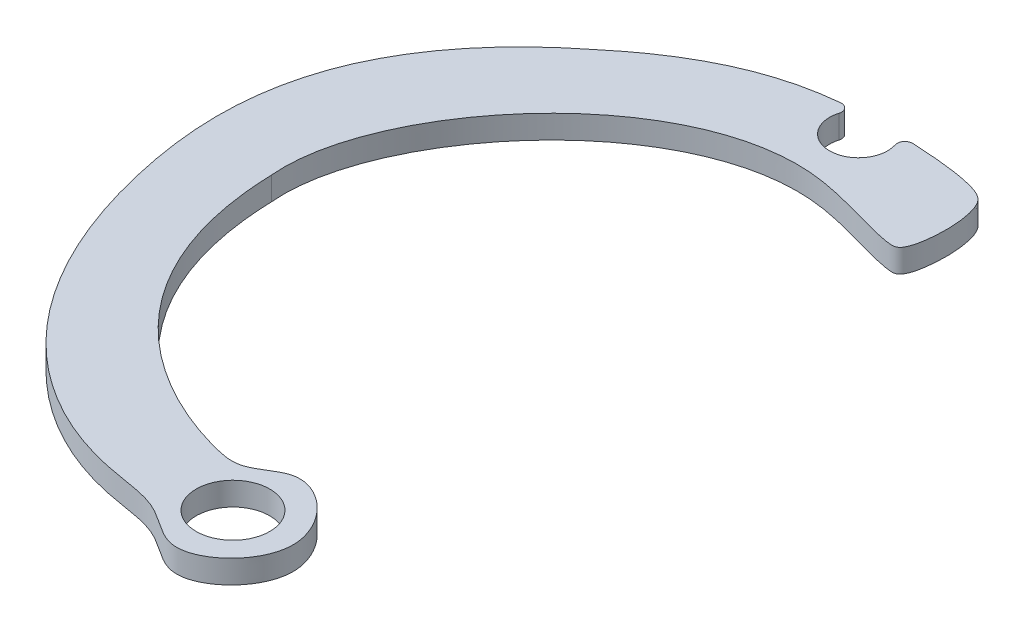
SolidWorks part; units mm, degrees
ref_plane "Front Plane" through (0, 0, 0) normal (0, 0, 1) x (1, 0, 0)
ref_plane "Top Plane" through (0, 0, 0) normal (0, 1, 0) x (1, 0, 0)
ref_plane "Right Plane" through (0, 0, 0) normal (1, 0, 0) x (0, 0, -1)
sketch "Sketch1" plane through (0, 0, 0) normal (0, 1, 0) x (1, 0, 0)
  line L1 (-28, 35) -> (28, 35) construction
  line L2 (-28, 35) -> (-28, 55) construction
  line L3 (-28, 55) -> (28, 55) construction
  line L4 (28, 35) -> (28, 55) construction
  line L5 (-28, 35) -> (28, 55) construction
  line L6 (-28, 55) -> (28, 35) construction
  circle A0 centre (0, 0) radius 35 construction
  circle A1 centre (0, 0) radius 40 construction
  circle A2 centre (0, 0) radius 45 construction
  circle A3 centre (0, -40) radius 7.75 construction
  spline S0 degree 3 poles (-35, 0) (-36.3595, 14.8311) (-14.1841, 42.3616) (10.1238, 32.2602) (14.7098, 32.0643) (15.1739, 40.8182) (12.2734, 44.1626) (0.2978, 45.5563) (-16.5396, 44.62) (-28, 35) knots 0 0 0 0 0.643737 0.804497 0.830881 0.899048 0.911987 0.951746 1 1 1 1
  spline S1 degree 3 poles (-28, 35) (-46.3291, 20.6392) (-47.0762, -19.7035) (-25.747, -42.3473) (-5.0885, -44.169) (0.8499, -50.48) (12.1162, -40.1687) (1.2506, -29.3596) (-3.7692, -34.971) (-12.9262, -33.4618) (-34.295, -24.3959) (-35, 0) knots 0 0 0 0 0.209604 0.538531 0.585123 0.63441 0.719791 0.805172 0.84714 0.866623 1 1 1 1
  point P7 (0, 45)
  point P15 (0, 0)
  point P19 (0, 0)
  point P22 (0, 0)
  point P23 (-27.3162, 35)
  point P25 (-35, -0.4792)
  point P27 (0, 0)
  dimension "D1" = 70
  dimension "D2" = 80
  dimension "D3" = 90
  dimension "D4" = 15.5
  dimension "D5" = 56
  dimension "D6" = 20
extrude "Boss-Extrude1" add sketch "Sketch1" along normal blind 3
sketch "Sketch2" plane through (0, 3, 0) normal (0, 1, 0) x (1, 0, 0)
  circle A0 centre (0, 0) radius 40 construction
  circle A1 centre (0, -40) radius 4.75
  dimension "D1" = 80
  dimension "D2" = 9.5
extrude "Cut-Extrude1" cut sketch "Sketch2" against normal blind 3
sketch "Sketch3" plane through (0, 3, 0) normal (0, 1, 0) x (1, 0, 0)
  circle A0 centre (-1.6734, 42.4548) radius 3.75
  dimension "D1" = 7.5
extrude "Cut-Extrude2" cut sketch "Sketch3" against normal blind 6
fillet "Fillet1" radius 1 2 edges at (-4.4795, 1.5, -44.9425) (1.1039, 1.5, -44.9745)
